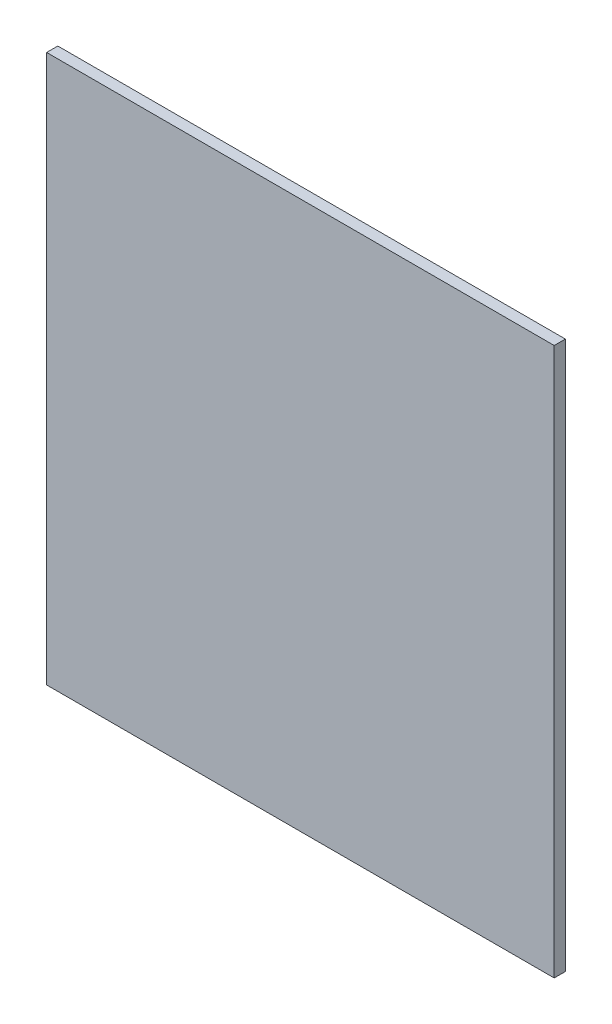
SolidWorks part; units mm, degrees
ref_plane "Front Plane" through (0, 0, 0) normal (0, 0, 1) x (1, 0, 0)
ref_plane "Top Plane" through (0, 0, 0) normal (0, 1, 0) x (1, 0, 0)
ref_plane "Right Plane" through (0, 0, 0) normal (1, 0, 0) x (0, 0, -1)
sketch "Sketch1" plane through (0, 0, 0) normal (0, 0, 1) x (1, 0, 0)
  line L1 (-23, 38.3) -> (33.8, 38.3)
  line L2 (-23, 38.3) -> (-23, -23)
  line L3 (-23, -23) -> (33.8, -23)
  line L4 (33.8, 38.3) -> (33.8, -23)
  dimension "D1" = 61.3
  dimension "D2" = 56.8
  dimension "D3" = 23
  dimension "D4" = 23
extrude "Boss-Extrude1" add sketch "Sketch1" along normal blind 1.25
